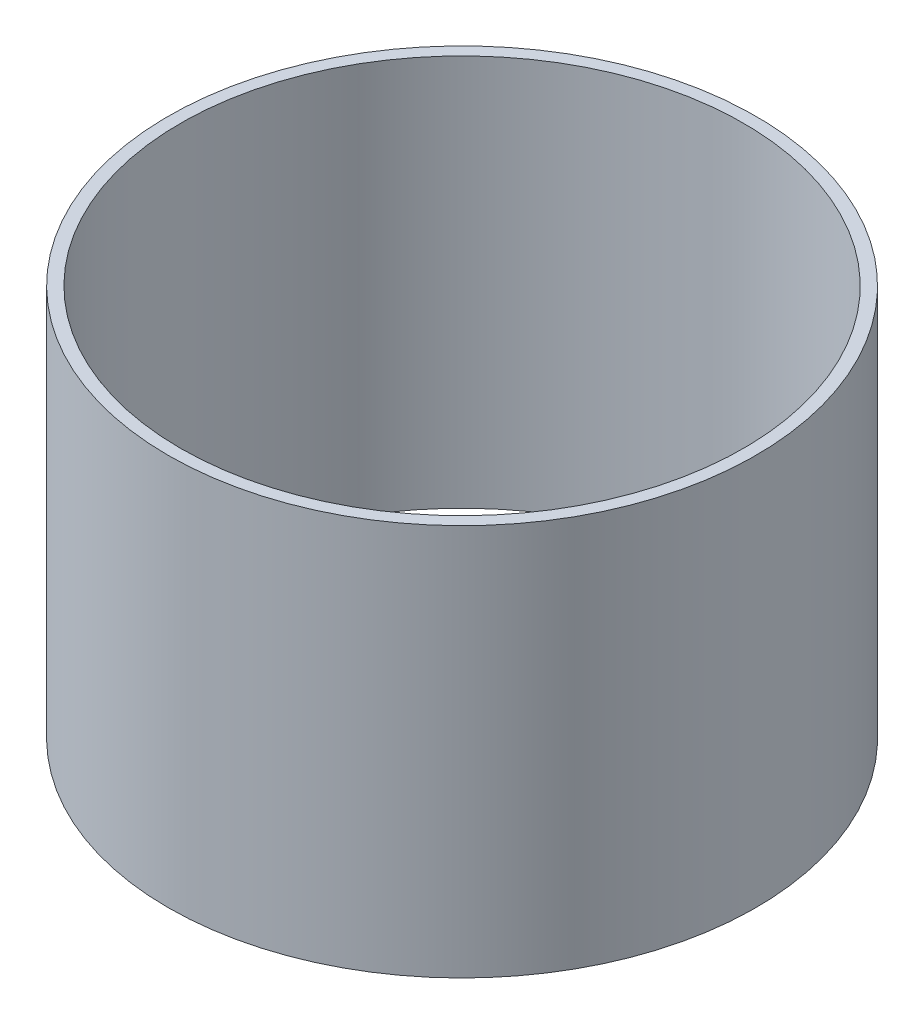
SolidWorks part; units mm, degrees
ref_plane "Front Plane" through (0, 0, 0) normal (0, 0, 1) x (1, 0, 0)
ref_plane "Top Plane" through (0, 0, 0) normal (0, 1, 0) x (1, 0, 0)
ref_plane "Right Plane" through (0, 0, 0) normal (1, 0, 0) x (0, 0, -1)
sketch "Sketch1" plane through (0, 0, 0) normal (0, 1, 0) x (1, 0, 0)
  circle A0 centre (0, 0) radius 73.025
  circle A1 centre (0, 0) radius 76.2
  dimension "D1" = 3.175
  dimension "D2" = 152.4
extrude "Boss-Extrude1" add sketch "Sketch1" along normal blind 101.6
